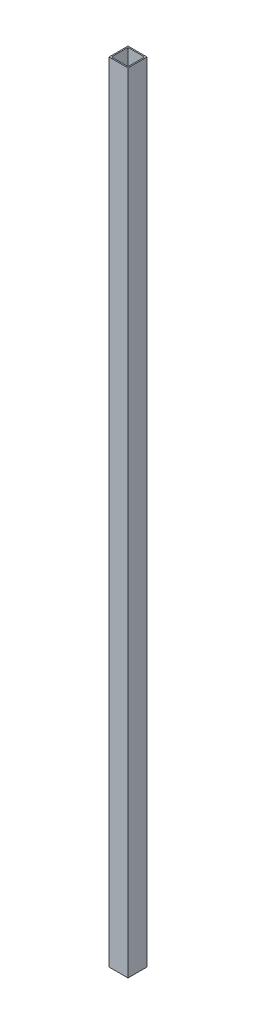
SolidWorks part; units mm, degrees
material "6061 Alloy"
ref_plane "Front Plane" through (0, 0, 0) normal (0, 0, 1) x (1, 0, 0)
ref_plane "Top Plane" through (0, 0, 0) normal (0, 1, 0) x (1, 0, 0)
ref_plane "Right Plane" through (0, 0, 0) normal (1, 0, 0) x (0, 0, -1)
sketch "Sketch1" plane through (0, 0, 0) normal (0, 1, 0) x (1, 0, 0)
  line L1 (12.7, 12.7) -> (-12.7, 12.7)
  line L2 (12.7, 12.7) -> (12.7, -12.7)
  line L3 (12.7, -12.7) -> (-12.7, -12.7)
  line L4 (-12.7, 12.7) -> (-12.7, -12.7)
  line L5 (12.7, 12.7) -> (-12.7, -12.7) construction
  line L6 (12.7, -12.7) -> (-12.7, 12.7) construction
  line L7 (11.1125, 11.1125) -> (-11.1125, 11.1125)
  line L8 (11.1125, 11.1125) -> (11.1125, -11.1125)
  line L9 (11.1125, -11.1125) -> (-11.1125, -11.1125)
  line L10 (-11.1125, 11.1125) -> (-11.1125, -11.1125)
  line L11 (11.1125, 11.1125) -> (-11.1125, -11.1125) construction
  line L12 (11.1125, -11.1125) -> (-11.1125, 11.1125) construction
  point P1 (0, 0)
  point P6 (0, 0)
  dimension "D1" = 25.4
  dimension "D2" = 25.4
  dimension "D3" = 1.5875
  dimension "D4" = 1.5875
extrude "Boss-Extrude1" add sketch "Sketch1" along normal blind 1054.1
